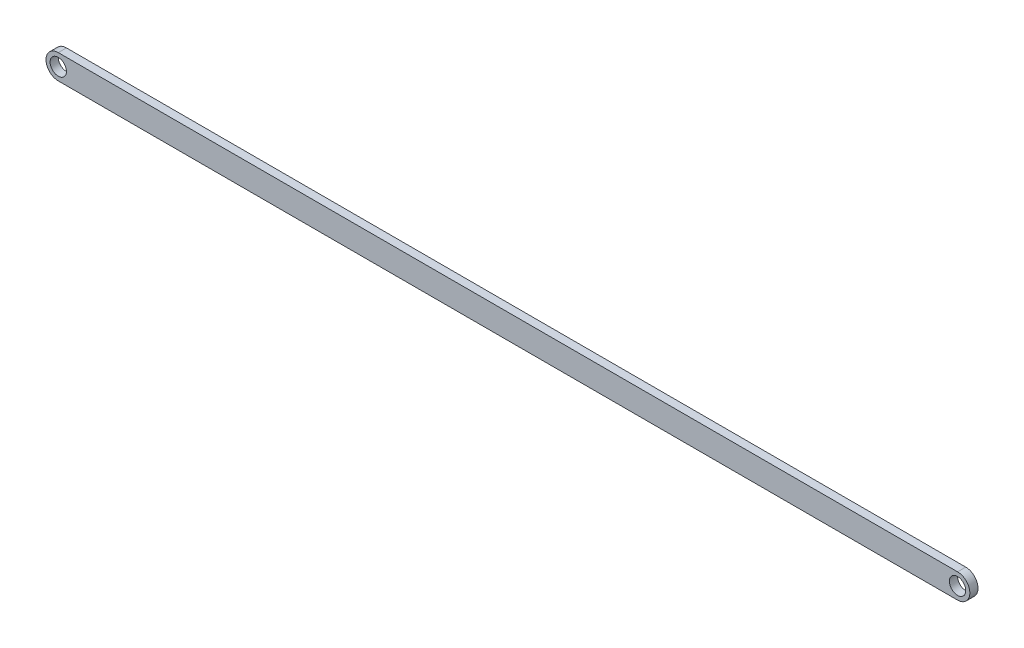
SolidWorks part; units mm, degrees
ref_plane "Front Plane" through (0, 0, 0) normal (0, 0, 1) x (1, 0, 0)
ref_plane "Top Plane" through (0, 0, 0) normal (0, 1, 0) x (1, 0, 0)
ref_plane "Right Plane" through (0, 0, 0) normal (1, 0, 0) x (0, 0, -1)
sketch "Sketch1" plane through (0, 0, 0) normal (0, 0, 1) x (1, 0, 0)
  line L0 (0, 0) -> (110, 0) construction
  line L1 (0, 1.5) -> (110, 1.5)
  line L2 (0, -1.5) -> (110, -1.5)
  arc A0 (0, 1.5) -> (0, -1.5) centre (0, 0) ccw
  arc A1 (110, -1.5) -> (110, 1.5) centre (110, 0) ccw
  point P3 (55, 0)
  dimension "D2" = 1.5
  dimension "D1" = 110
extrude "Boss-Extrude1" add sketch "Sketch1" along normal blind 1
sketch "Sketch2" plane through (0, 0, 1) normal (0, 0, 1) x (1, 0, 0)
  circle A0 centre (0, 0) radius 1
  circle A1 centre (110, 0) radius 1
  dimension "D1" = 2
extrude "Cut-Extrude2" cut sketch "Sketch2" against normal up to next
